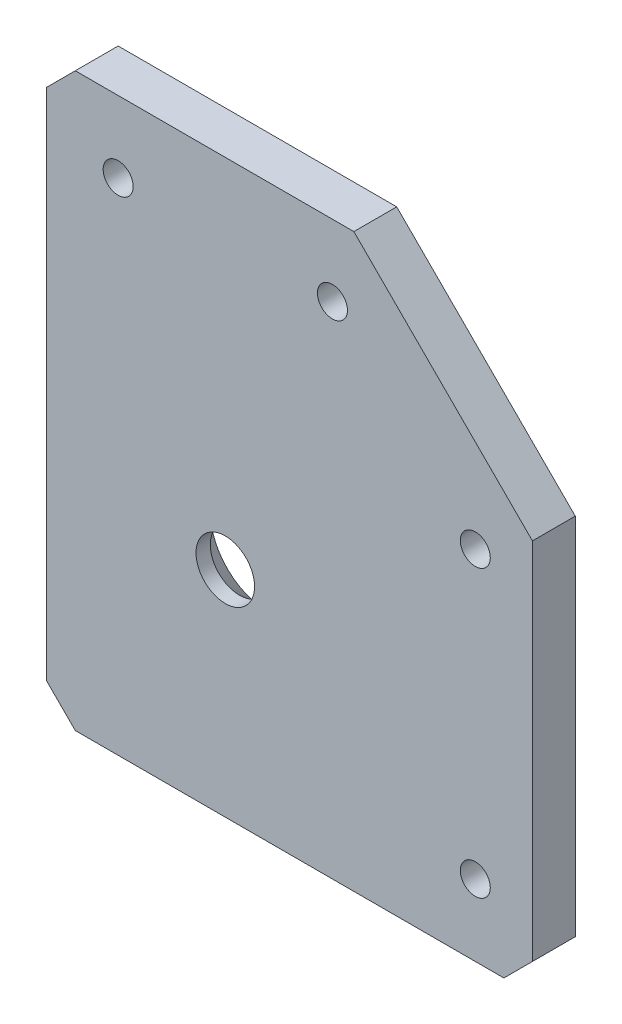
SolidWorks part; units mm, degrees
ref_plane "前视基准面" through (0, 0, 0) normal (0, 0, 1) x (1, 0, 0)
ref_plane "上视基准面" through (0, 0, 0) normal (0, 1, 0) x (1, 0, 0)
ref_plane "右视基准面" through (0, 0, 0) normal (1, 0, 0) x (0, 0, -1)
sketch "草图1" plane through (0, 0, 0) normal (0, 0, 1) x (1, 0, 0)
  line L0 (35, 20) -> (35, -20) construction
  line L1 (43, -30) -> (-25, -30)
  line L2 (43, -30) -> (43, 50)
  line L3 (43, 50) -> (-25, 50)
  line L4 (-25, -30) -> (-25, 50)
  line L5 (43, -30) -> (-25, 50) construction
  line L6 (43, 50) -> (-25, -30) construction
  line L7 (-15, 40) -> (15, 40) construction
  circle A0 centre (0, 0) radius 4.1
  circle A1 centre (35, 20) radius 2.1
  circle A2 centre (35, -20) radius 2.1
  circle A3 centre (-15, 40) radius 2.1
  circle A4 centre (15, 40) radius 2.1
  point P3 (9, 10)
  point P12 (35, 0)
  point P17 (0, 40)
  point P18 (9, 50)
  dimension "D1" = 50
  dimension "D2" = 8.2
  dimension "D3" = 4.2
  dimension "D6" = 25
  dimension "D8" = 10
  dimension "D9" = 10
  dimension "D4" = 40
  dimension "D5" = 35
  dimension "D7" = 8
  dimension "D10" = 10
extrude "凸台-拉伸1" add sketch "草图1" along normal mid plane 6
chamfer "倒角1" distance 25 angle 45 1 edges at (43, 50, 0)
chamfer "倒角2" distance 4 angle 45 4 edges at (-25, 50, 0) (43, -30, 0) (-25, -30, 0) (4.1, 0, -3)
chamfer "倒角3" distance 2 angle 45 4 edges at (37.1, -20, -3) (37.1, 20, -3) (17.1, 40, -3) (-12.9, 40, -3)
